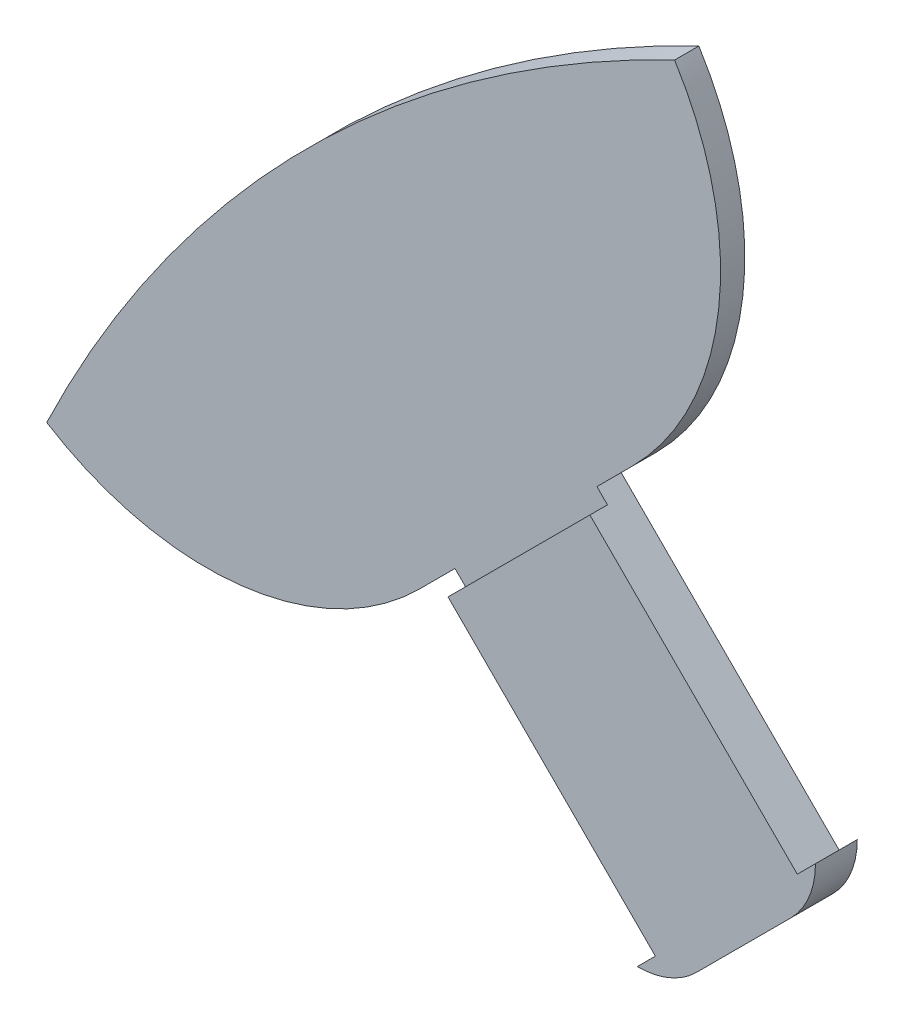
SolidWorks part; units mm, degrees
ref_plane "Front Plane" through (0, 0, 0) normal (0, 0, 1) x (1, 0, 0)
ref_plane "Top Plane" through (0, 0, 0) normal (0, 1, 0) x (1, 0, 0)
ref_plane "Right Plane" through (0, 0, 0) normal (1, 0, 0) x (0, 0, -1)
sketch "Sketch1" plane through (0, 0, 0) normal (0, 0, 1) x (1, 0, 0)
  line L0 (0, 80) -> (0, -80) construction
  line L1 (-80, 0) -> (80, 0) construction
  line L2 (9, -46.6) -> (9, -79.4921)
  line L3 (-4, 41.6) -> (4, 41.6)
  line L4 (-9, 46.6) -> (-9, 79.4921)
  line L6 (9, 46.6) -> (9, 79.4921)
  line L7 (-4, -41.6) -> (4, -41.6)
  line L8 (-9, -46.6) -> (-9, -79.4921)
  line L9 (41.6, 4) -> (41.6, -4)
  line L10 (46.6, -9) -> (79.4921, -9)
  line L11 (46.6, 9) -> (79.4921, 9)
  line L12 (-46.6, -9) -> (-79.4921, -9)
  line L13 (-41.6, 4) -> (-41.6, -4)
  line L14 (-46.6, 9) -> (-79.4921, 9)
  line L15 (26.5872, 32.2441) -> (32.2441, 26.5872)
  line L16 (39.3151, 26.5872) -> (62.5734, 49.8455)
  line L17 (26.5872, 39.3151) -> (49.8455, 62.5734)
  line L18 (-26.5872, 39.3151) -> (-49.8455, 62.5734)
  line L19 (-26.5872, 32.2441) -> (-32.2441, 26.5872)
  line L20 (-39.3151, 26.5872) -> (-62.5734, 49.8455)
  line L21 (0, 0) -> (56.5685, 56.5685) construction
  line L22 (0, 0) -> (-56.5685, 56.5685) construction
  line L23 (-26.5872, -39.3151) -> (-49.8455, -62.5734)
  line L24 (-26.5872, -32.2441) -> (-32.2441, -26.5872)
  line L25 (-39.3151, -26.5872) -> (-62.5734, -49.8455)
  line L26 (26.5872, -39.3151) -> (49.8455, -62.5734)
  line L27 (26.5872, -32.2441) -> (32.2441, -26.5872)
  line L28 (39.3151, -26.5872) -> (62.5734, -49.8455)
  line L29 (-37.1175, 49.8455) -> (-49.8455, 37.1175)
  line L30 (-35.7796, 25.1227) -> (-25.1227, 35.7796)
  line L31 (-47.7241, 39.2389) -> (-34.6938, 26.2085)
  line L32 (-39.2389, 47.7241) -> (-26.2085, 34.6938)
  circle A0 centre (0, 0) radius 80
  arc A1 (41.6, 4) -> (46.6, 9) centre (46.6, 4) cw
  arc A2 (41.6, -4) -> (46.6, -9) centre (46.6, -4) ccw
  arc A3 (32.2441, -26.5872) -> (39.3151, -26.5872) centre (35.7796, -30.1227) cw
  arc A4 (26.5872, -32.2441) -> (26.5872, -39.3151) centre (30.1227, -35.7796) ccw
  arc A5 (4, -41.6) -> (9, -46.6) centre (4, -46.6) cw
  arc A6 (-4, -41.6) -> (-9, -46.6) centre (-4, -46.6) ccw
  arc A7 (-26.5872, -32.2441) -> (-26.5872, -39.3151) centre (-30.1227, -35.7796) cw
  arc A8 (-32.2441, -26.5872) -> (-39.3151, -26.5872) centre (-35.7796, -30.1227) ccw
  arc A9 (-46.6, -9) -> (-41.6, -4) centre (-46.6, -4) ccw
  arc A10 (-41.6, 4) -> (-46.6, 9) centre (-46.6, 4) ccw
  arc A11 (-26.5872, 39.3151) -> (-26.5872, 32.2441) centre (-30.1227, 35.7796) cw
  arc A12 (-32.2441, 26.5872) -> (-39.3151, 26.5872) centre (-35.7796, 30.1227) cw
  arc A13 (-4, 41.6) -> (-9, 46.6) centre (-4, 46.6) cw
  arc A14 (4, 41.6) -> (9, 46.6) centre (4, 46.6) ccw
  arc A15 (32.2441, 26.5872) -> (39.3151, 26.5872) centre (35.7796, 30.1227) ccw
  arc A16 (26.5872, 32.2441) -> (26.5872, 39.3151) centre (30.1227, 35.7796) cw
  arc A17 (34.5941, 72.1335) -> (37.1175, 49.8455) centre (49.8455, 62.5734) ccw
  arc A18 (49.8455, 37.1175) -> (72.1335, 34.5941) centre (62.5734, 49.8455) ccw
  arc A19 (-34.5941, 72.1335) -> (-37.1175, 49.8455) centre (-49.8455, 62.5734) cw
  arc A20 (-49.8455, 37.1175) -> (-72.1335, 34.5941) centre (-62.5734, 49.8455) cw
  arc A21 (-49.8455, -37.1175) -> (-72.1335, -34.5941) centre (-62.5734, -49.8455) ccw
  arc A22 (-34.5941, -72.1335) -> (-37.1175, -49.8455) centre (-49.8455, -62.5734) ccw
  arc A23 (34.5941, -72.1335) -> (37.1175, -49.8455) centre (49.8455, -62.5734) cw
  arc A24 (49.8455, -37.1175) -> (72.1335, -34.5941) centre (62.5734, -49.8455) cw
  arc A25 (-26.5444, 75.4678) -> (-9, 61.4921) centre (-9, 79.4921) ccw
  arc A26 (9, 61.4921) -> (26.5444, 75.4678) centre (9, 79.4921) ccw
  arc A27 (-26.5444, -75.4678) -> (-9, -61.4921) centre (-9, -79.4921) cw
  arc A28 (9, -61.4921) -> (26.5444, -75.4678) centre (9, -79.4921) cw
  arc A29 (-61.4921, 9) -> (-75.4678, 26.5444) centre (-79.4921, 9) ccw
  arc A30 (-75.4678, -26.5444) -> (-61.4921, -9) centre (-79.4921, -9) ccw
  arc A31 (61.4921, 9) -> (75.4678, 26.5444) centre (79.4921, 9) cw
  arc A32 (75.4678, -26.5444) -> (61.4921, -9) centre (79.4921, -9) cw
  circle A33 centre (0, 0) radius 11
  point P44 (41.6, 9)
  point P47 (41.6, -9)
  point P50 (35.7796, -23.0517)
  point P53 (23.0517, -35.7796)
  point P56 (9, -41.6)
  point P59 (-9, -41.6)
  point P62 (-23.0517, -35.7796)
  point P65 (-35.7796, -23.0517)
  point P68 (-41.6, -9)
  point P71 (-41.6, 9)
  point P74 (-23.0517, 35.7796)
  point P77 (-35.7796, 23.0517)
  point P80 (-9, 41.6)
  point P83 (9, 41.6)
  point P86 (35.7796, 23.0517)
  point P89 (23.0517, 35.7796)
  dimension "D1" = 160
  dimension "D13" = 5
  dimension "D14" = 18
  dimension "D15" = 18
  dimension "D16" = 18
  dimension "D17" = 18
  dimension "D18" = 18
  dimension "D20" = 22
  dimension "D2" = 41.6
  dimension "D3" = 41.6
  dimension "D4" = 41.6
  dimension "D5" = 9
  dimension "D6" = 9
  dimension "D7" = 9
  dimension "D8" = 45
  dimension "D9" = 45
  dimension "D10" = 9
  dimension "D11" = 9
  dimension "D12" = 9
  dimension "D19" = 18
  dimension "D21" = 3
  dimension "D22" = 3
extrude "Boss-Extrude2" add sketch "Sketch1" along normal blind 5 contours L32 L29 L31 L30 | L18 A0 L20 L29 | A19 A0 L18 | A20 L20 A0 | A12 L19 A11 L30
ref_plane "Plane1" through (-57.6999, 57.6999, 0) normal (0.7071, -0.7071, 0) x (-0.7071, -0.7071, 0)
sketch "Sketch3" plane through (-57.6999, 57.6999, 0) normal (0.7071, -0.7071, 0) x (-0.7071, -0.7071, 0)
  line L0 (9, 0) -> (6, 0) construction
  line L1 (6, 0) -> (6, -5) construction
  line L2 (6, -5) -> (9, -5) construction
  line L3 (9, -5) -> (9, 0) construction
  line L4 (26.5444, 0) -> (9, 0)
  line L5 (9, 0) -> (9, -5)
  line L6 (9, -5) -> (26.5444, -5)
  line L7 (26.5444, -5) -> (26.5444, 0)
  line L8 (26.5444, 0) -> (9, 0)
  line L9 (9, 0) -> (9, -5)
  line L10 (9, -5) -> (26.5444, -5)
  line L11 (26.5444, -5) -> (26.5444, 0)
  line L12 (7.5355, 0) -> (4, 0) construction
  line L13 (4, -5) -> (7.5355, -5) construction
  line L14 (7.5355, -5) -> (7.5355, 0) construction
  line L15 (4, 0) -> (-4, 0) construction
  line L16 (-4, -5) -> (4, -5) construction
  line L17 (-4, 0) -> (-7.5355, 0) construction
  line L18 (-7.5355, 0) -> (-7.5355, -5) construction
  line L19 (-7.5355, -5) -> (-4, -5) construction
  line L20 (-6, 0) -> (-9, 0) construction
  line L21 (-9, -5) -> (-6, -5) construction
  line L22 (-6, -5) -> (-6, 0) construction
  line L23 (-9, 0) -> (-26.5444, 0) construction
  line L24 (-26.5444, 0) -> (-26.5444, -5) construction
  line L25 (-26.5444, -5) -> (-9, -5) construction
  line L26 (9, 0) -> (6, 0)
  line L27 (6, 0) -> (6, -5)
  line L28 (6, -5) -> (9, -5)
  line L29 (9, -5) -> (9, 0)
  line L30 (7.5355, 0) -> (4, 0)
  line L31 (4, -5) -> (7.5355, -5)
  line L32 (7.5355, -5) -> (7.5355, 0)
  line L33 (4, 0) -> (-4, 0)
  line L34 (-4, -5) -> (4, -5)
  line L35 (-4, 0) -> (-7.5355, 0)
  line L36 (-7.5355, 0) -> (-7.5355, -5)
  line L37 (-7.5355, -5) -> (-4, -5)
  line L38 (-6, 0) -> (-9, 0)
  line L39 (-9, -5) -> (-6, -5)
  line L40 (-6, -5) -> (-6, 0)
  line L41 (-9, 0) -> (-26.5444, 0)
  line L42 (-26.5444, 0) -> (-26.5444, -5)
  line L43 (-26.5444, -5) -> (-9, -5)
  line L45 (26.5444, -3.55) -> (-26.5444, -3.55)
  line L46 (26.5444, -3.55) -> (26.5444, -1.45)
  line L47 (26.5444, -1.45) -> (-26.5444, -1.45)
  line L48 (-26.5444, -3.55) -> (-26.5444, -1.45)
  dimension "D1" = 0
  dimension "D2" = 1.45
  dimension "D3" = 1.45
extrude "Cut-Extrude1" cut sketch "Sketch3" along normal blind 16 from offset 5 contours L36 L47 L42 L45 | L27 L47 L40 L45 | L40 L47 L36 L45 | L32 L47 L27 L45 | L29 L47 L32 L45 | L11 L47 L29 L45
sketch "Sketch4" plane through (-57.6999, 57.6999, 0) normal (0.7071, -0.7071, 0) x (-0.7071, -0.7071, 0)
  line L0 (-7.5355, -5) -> (-7.5355, 0) construction
  line L1 (-7.5355, -5) -> (-7.5355, 0)
  line L2 (-7.5355, -2.5) -> (27.0542, -2.5)
  line L3 (27.0542, -2.5) -> (27.0542, -6.9729)
  line L4 (27.0542, -6.9729) -> (-28.0745, -6.9729)
  line L5 (-28.0745, -6.9729) -> (-28.0745, -2.5)
  line L6 (-28.0745, -2.5) -> (-7.5355, -2.5)
extrude "Cut-Extrude2" cut sketch "Sketch4" along normal blind 52
sketch "Sketch5" plane through (-54.1644, 54.1644, 0) normal (0.7071, -0.7071, 0) x (0, 0, -1)
  line L0 (-2.5, -23.0747) -> (-2.5, 23.0747) construction
  line L1 (-2.5, -23.0747) -> (-1.45, -23.0747) construction
  line L2 (-1.45, -23.0747) -> (-1.45, 23.0747) construction
  line L3 (-1.45, 23.0747) -> (-2.5, 23.0747) construction
  line L4 (-2.5, -23.0747) -> (-2.5, 23.0747)
  line L5 (-2.5, -23.0747) -> (-1.45, -23.0747)
  line L6 (-1.45, -23.0747) -> (-1.45, 23.0747)
  line L7 (-1.45, 23.0747) -> (-2.5, 23.0747)
extrude "Cut-Extrude3" cut sketch "Sketch5" against normal blind 10
